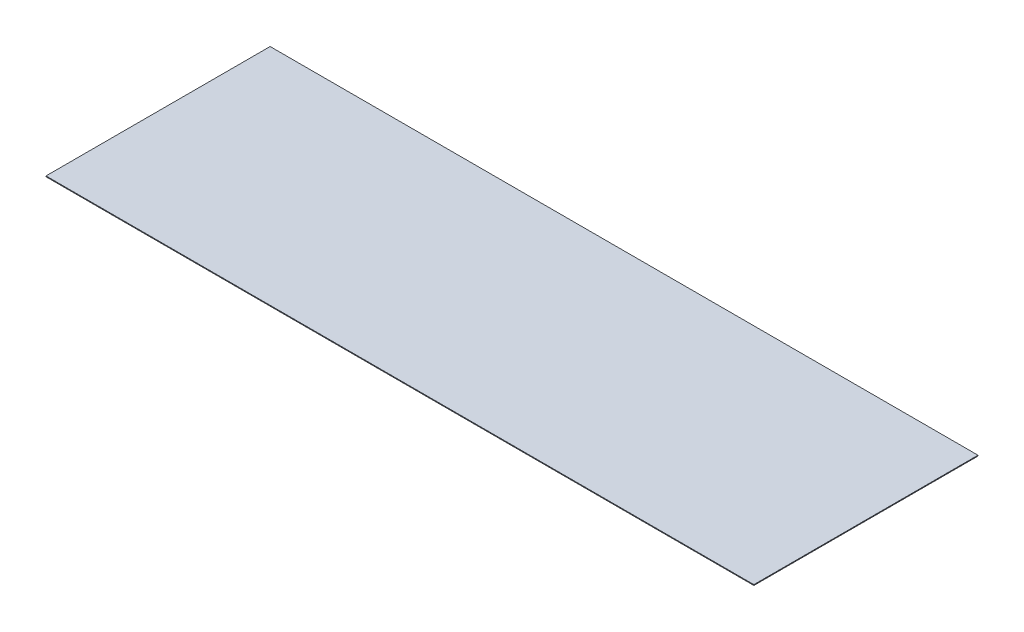
SolidWorks part; units mm, degrees
ref_plane "Front Plane" through (0, 0, 0) normal (0, 0, 1) x (1, 0, 0)
ref_plane "Top Plane" through (0, 0, 0) normal (0, 1, 0) x (1, 0, 0)
ref_plane "Right Plane" through (0, 0, 0) normal (1, 0, 0) x (0, 0, -1)
sketch "Sketch1" plane through (0, 0, 0) normal (0, 1, 0) x (1, 0, 0)
  line L0 (-260.5254, -88.68) -> (299.665, -88.68)
  line L1 (-260.5254, -88.68) -> (-260.5254, 88.68)
  line L2 (299.665, -88.68) -> (299.665, 88.68)
  line L3 (-260.5254, 88.68) -> (299.665, 88.68)
  line L4 (-260.5254, -88.68) -> (299.665, 88.68) construction
  line L5 (299.665, -88.68) -> (-260.5254, 88.68) construction
  line L6 (299.665, -89.2896) -> (299.665, 239.5364) construction
  line L7 (-260.5254, -273.6028) -> (-260.5254, 240.146) construction
  point P1 (0, 0)
  dimension "D1" = 177.36
extrude "Boss-Extrude1" add sketch "Sketch1" along normal blind 0.6096
